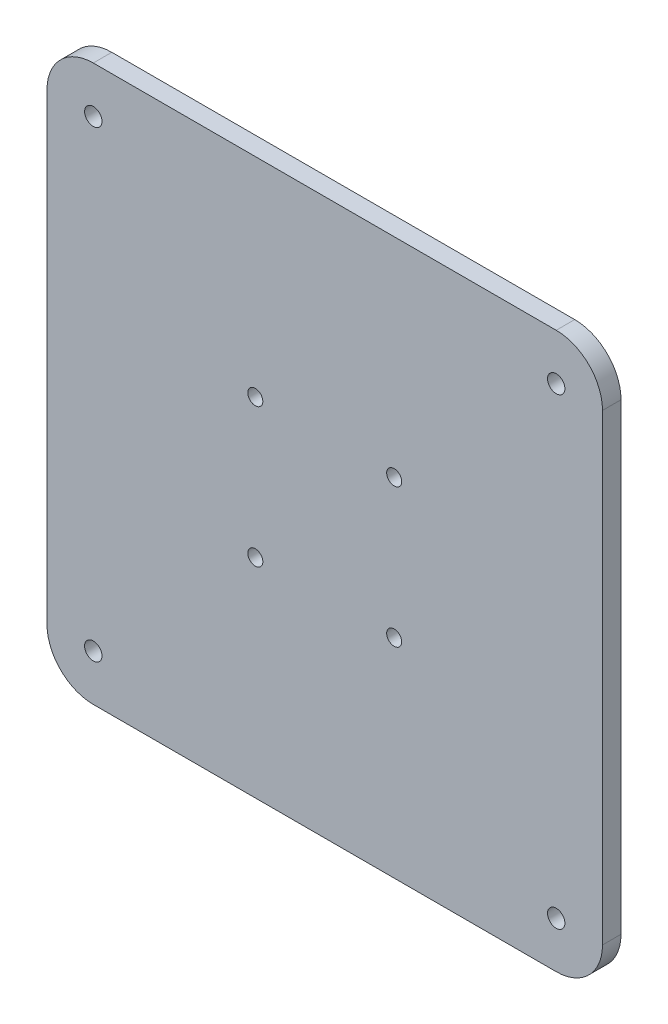
SolidWorks part; units mm, degrees
ref_plane "前视基准面" through (0, 0, 0) normal (0, 0, 1) x (1, 0, 0)
ref_plane "上视基准面" through (0, 0, 0) normal (0, 1, 0) x (1, 0, 0)
ref_plane "右视基准面" through (0, 0, 0) normal (1, 0, 0) x (0, 0, -1)
other "Configuration Table"
sketch "草图1" plane through (0, 0, 0) normal (0, 0, 1) x (1, 0, 0)
  line L0 (0, 0) -> (284.1069, 0) construction
  line L1 (-120, 120) -> (120, 120)
  line L2 (-120, 120) -> (-120, -120)
  line L3 (-120, -120) -> (120, -120)
  line L4 (120, 120) -> (120, -120)
  line L5 (0, 0) -> (0, 194.938) construction
  circle A0 centre (30, 30) radius 3.25
  circle A1 centre (30, -30) radius 3.25
  circle A2 centre (-30, 30) radius 3.25
  circle A3 centre (-30, -30) radius 3.25
  circle A4 centre (100, 100) radius 3.75
  circle A6 centre (100, -100) radius 3.75
  circle A7 centre (-100, -100) radius 3.75
  circle A8 centre (-100, 100) radius 3.75
  dimension "D3" = 6.5
  dimension "D6" = 7.5
  dimension "D1" = 240
  dimension "D2" = 240
  dimension "D4" = 30
  dimension "D5" = 30
  dimension "D7" = 20
  dimension "D8" = 20
extrude "凸台-拉伸1" add sketch "草图1" along normal blind 8 contours L4 L3 L2 L1 | A1 | A3 | A2 | A0 | A6 | A7 | A8 | A4
fillet "圆角1" radius 20 4 edges at (-120, 120, 4) (-120, -120, 4) (120, -120, 4) (120, 120, 4)
